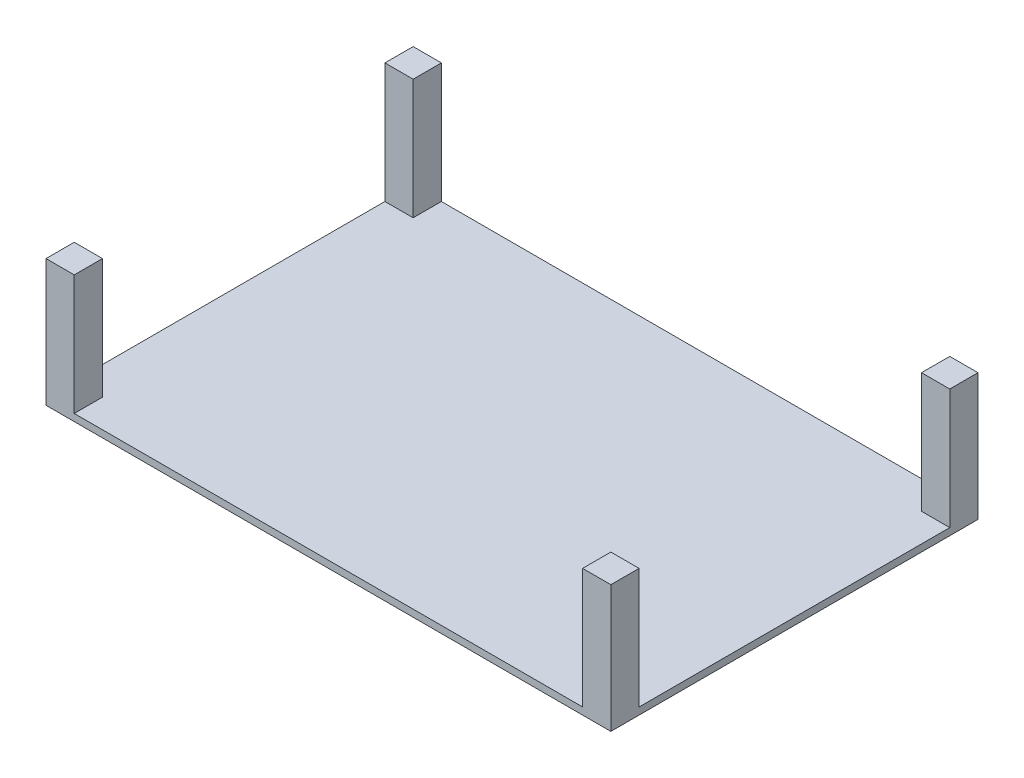
SolidWorks part; units mm, degrees
ref_plane "Front Plane" through (0, 0, 0) normal (0, 0, 1) x (1, 0, 0)
ref_plane "Top Plane" through (0, 0, 0) normal (0, 1, 0) x (1, 0, 0)
ref_plane "Right Plane" through (0, 0, 0) normal (1, 0, 0) x (0, 0, -1)
sketch "Sketch2" plane through (0, 0, 0) normal (0, 1, 0) x (1, 0, 0)
  line L1 (-127, -82.55) -> (127, -82.55)
  line L2 (-127, -82.55) -> (-127, 82.55)
  line L3 (-127, 82.55) -> (127, 82.55)
  line L4 (127, -82.55) -> (127, 82.55)
  line L5 (-127, -82.55) -> (127, 82.55) construction
  line L6 (-127, 82.55) -> (127, -82.55) construction
  point P0 (0, 0)
  dimension "D1" = 165.1
  dimension "D2" = 254
extrude "Boss-Extrude1" add sketch "Sketch2" along normal blind 3.175
sketch "Sketch3" plane through (0, 3.175, 0) normal (0, 1, 0) x (1, 0, 0)
  line L1 (-127, -82.55) -> (-114.3, -82.55)
  line L2 (-127, -82.55) -> (-127, -69.85)
  line L3 (-127, -69.85) -> (-114.3, -69.85)
  line L4 (-114.3, -82.55) -> (-114.3, -69.85)
  dimension "D1" = 12.7
  dimension "D2" = 12.7
extrude "Boss-Extrude2" add sketch "Sketch3" along normal blind 53.975
pattern_linear "LPattern1" count 2 spacing 152.4 along (0, 0, -1) count 2 spacing 241.3 along (1, 0, 0) of "Boss-Extrude2"
